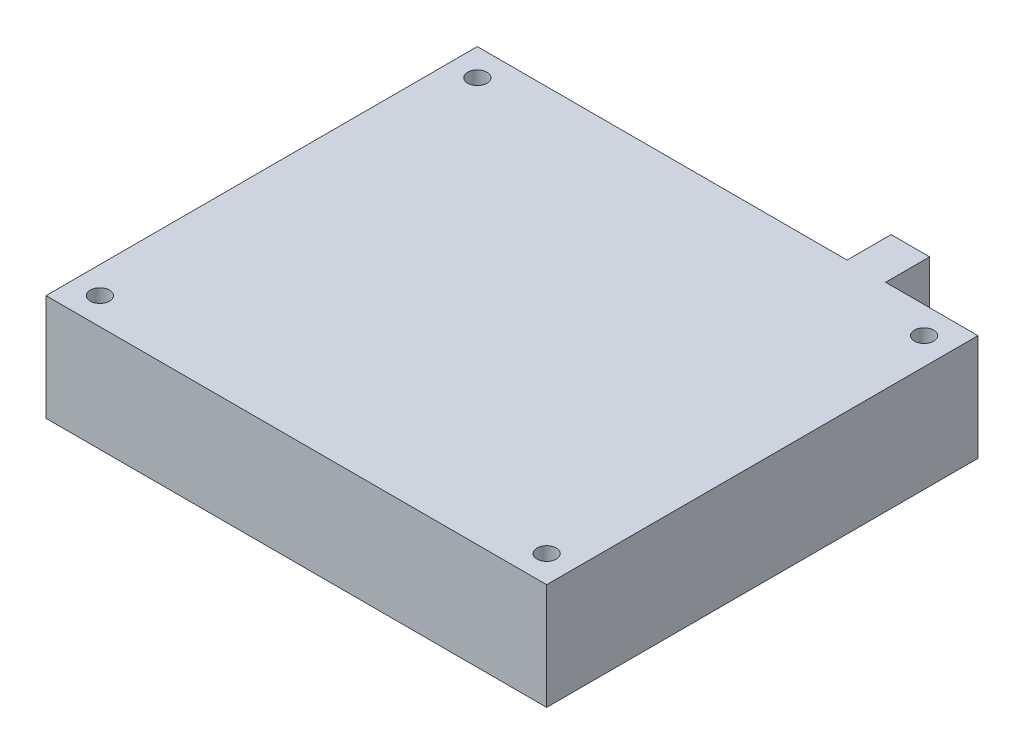
SolidWorks part; units mm, degrees
ref_plane "前视基准面" through (0, 0, 0) normal (0, 0, 1) x (1, 0, 0)
ref_plane "上视基准面" through (0, 0, 0) normal (0, 1, 0) x (1, 0, 0)
ref_plane "右视基准面" through (0, 0, 0) normal (1, 0, 0) x (0, 0, -1)
other "Configuration Table"
sketch "草图2" plane through (0, 0, 0) normal (0, 1, 0) x (1, 0, 0)
  line L0 (-32.5, 28) -> (15.5, 28)
  line L1 (15.5, 28) -> (15.5, 33.72)
  line L2 (15.5, 33.72) -> (20.5, 33.72)
  line L3 (20.5, 33.72) -> (20.5, 28)
  line L4 (20.5, 28) -> (32.5, 28)
  line L5 (32.5, 28) -> (32.5, -28)
  line L6 (32.5, -28) -> (-32.5, -28)
  line L7 (-32.5, -28) -> (-32.5, 28)
  circle A0 centre (-29, 24.5) radius 1.25
  circle A1 centre (-29, -24.5) radius 1.25
  circle A2 centre (29, 24.5) radius 1.25
  circle A3 centre (29, -24.5) radius 1.25
extrude "凸台-拉伸1" add sketch "草图2" along normal blind 13.8
